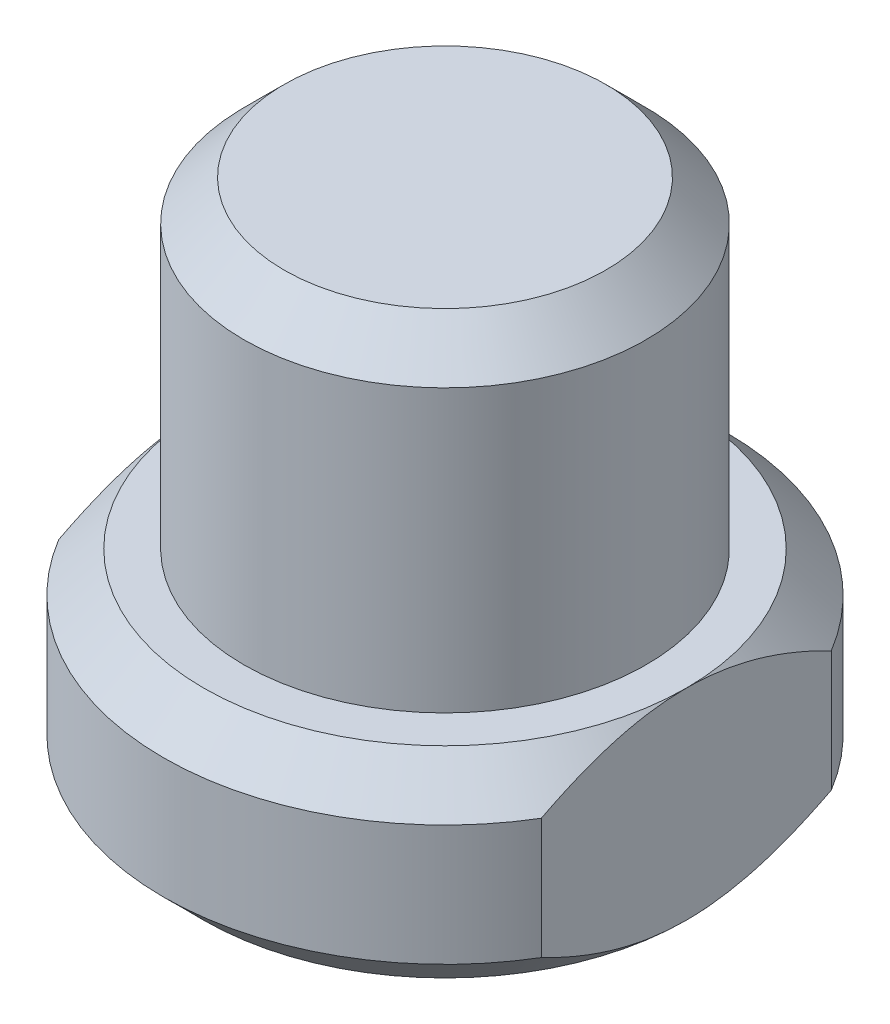
SolidWorks part; units mm, degrees
other "Detailelement1"
material "1.4404 (X2CrNiMo17-12-2"
ref_plane "Vorne" through (0, 0, 0) normal (0, 0, 1) x (1, 0, 0)
ref_plane "Oben" through (0, 0, 0) normal (0, 1, 0) x (1, 0, 0)
ref_plane "Rechts" through (0, 0, 0) normal (1, 0, 0) x (0, 0, -1)
sketch "Skizze2" plane through (0, 0, 0) normal (1, 0, 0) x (0, 0, -1)
  line L0 (0, 0) -> (6, 0)
  line L1 (0, 0) -> (0, 13)
  line L2 (0, 0) -> (0, -26.8533) construction
  line L3 (7, 4) -> (6, 5)
  line L4 (7, 1) -> (7, 4)
  line L5 (6, 5) -> (5, 5)
  line L6 (-0.0736, 0) -> (0, 0) construction
  line L7 (5, 5) -> (5, 12)
  line L8 (5, 12) -> (4, 13)
  line L9 (4, 13) -> (0, 13)
  line L10 (6, 0) -> (7, 1)
  point P8 (7, 5)
  dimension "D2" = 14
  dimension "D3" = 10
  dimension "D4" = 13
  dimension "D5" = 8
  dimension "D6" = 1
  dimension "D7" = 45
  dimension "D9" = 4
  dimension "D11" = 45
revolve "Rotation1" add sketch "Skizze2" angle 360 about L2
cosmetic thread "Gewindedarstellung1" parameters "D1"=10, "D2"=8.891
sketch "Skizze3" plane through (0, 5, 0) normal (0, 1, 0) x (1, 0, 0)
  line L0 (0, 0) -> (0, 17.7856) construction
  line L1 (11, 11.5) -> (6, 11.5)
  line L2 (11, 11.5) -> (11, -11.5)
  line L3 (11, -11.5) -> (6, -11.5)
  line L4 (6, 11.5) -> (6, -11.5)
  line L5 (-6, 11.5) -> (-6, -11.5)
  line L6 (-11, -11.5) -> (-6, -11.5)
  line L7 (-11, 11.5) -> (-11, -11.5)
  line L8 (-11, 11.5) -> (-6, 11.5)
  line L9 (6, 0) -> (0, 0) construction
  dimension "D1" = 12
  dimension "D2" = 5
  dimension "D3" = 23
extrude "Schnitt-Linear austragen1" cut sketch "Skizze3" against normal blind 9
